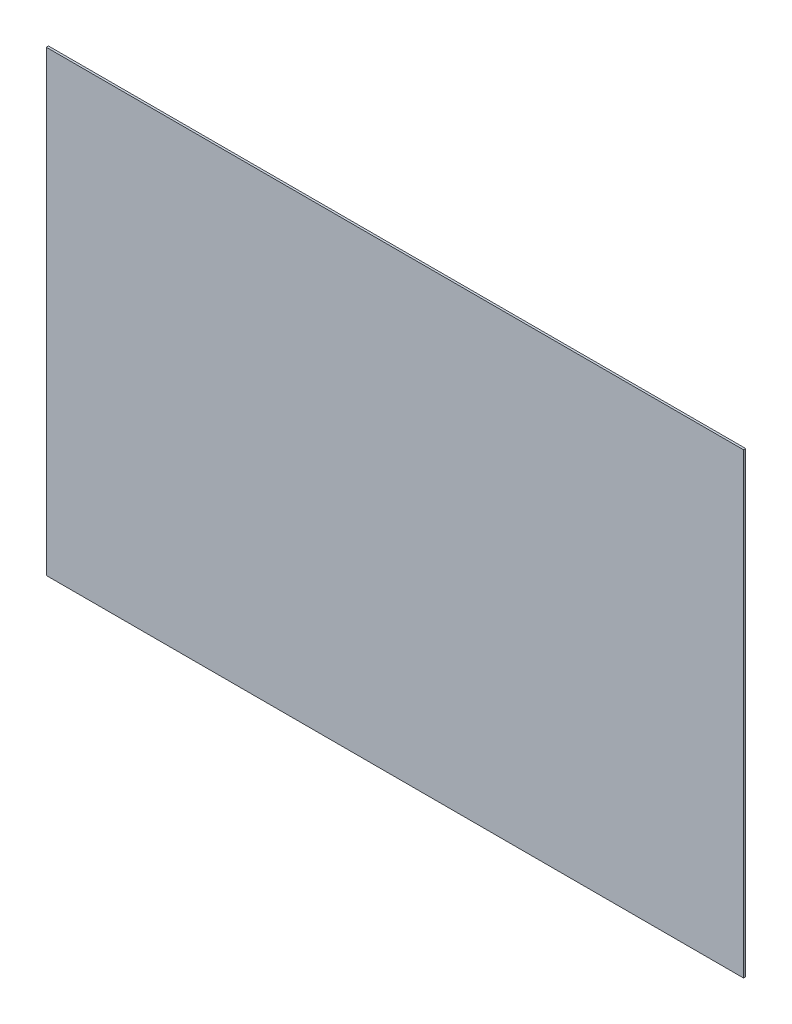
SolidWorks part; units mm, degrees
ref_plane "前视基准面" through (0, 0, 0) normal (0, 0, 1) x (1, 0, 0)
ref_plane "上视基准面" through (0, 0, 0) normal (0, 1, 0) x (1, 0, 0)
ref_plane "右视基准面" through (0, 0, 0) normal (1, 0, 0) x (0, 0, -1)
sketch "草图1" plane through (0, 0, 0) normal (0, 0, 1) x (1, 0, 0)
  line L1 (0, 0) -> (-320, 0)
  line L2 (0, 0) -> (0, 210)
  line L3 (0, 210) -> (-320, 210)
  line L4 (-320, 0) -> (-320, 210)
  dimension "D1" = 320
  dimension "D2" = 210
extrude "凸台-拉伸1" add sketch "草图1" along normal blind 1
